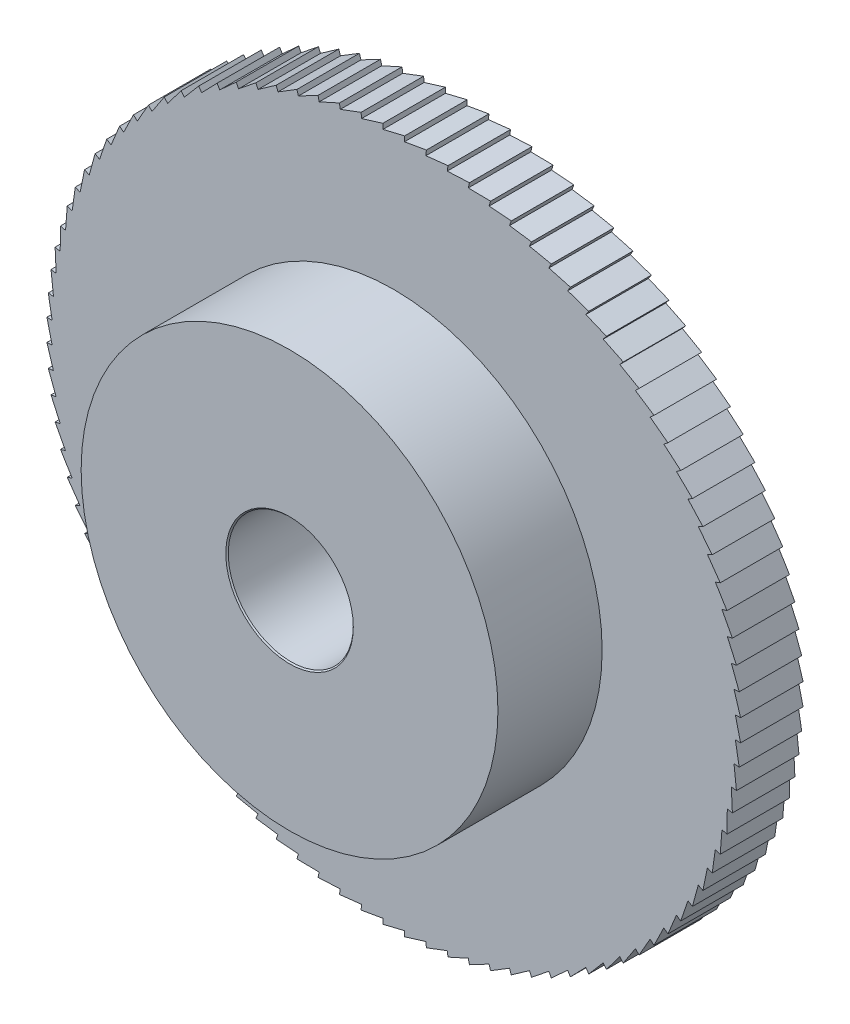
SolidWorks part; units mm, degrees
ref_plane "Front" through (0, 0, 0) normal (0, 0, 1) x (1, 0, 0)
ref_plane "Top" through (0, 0, 0) normal (0, 1, 0) x (1, 0, 0)
ref_plane "Right" through (0, 0, 0) normal (1, 0, 0) x (0, 0, -1)
sketch "Sketch1" plane through (0, 0, 0) normal (0, 0, 1) x (1, 0, 0)
  line L0 (-50, 0) -> (50, 0) construction
  circle A0 centre (0, 0) radius 33.3 construction
  circle A1 centre (0, 0) radius 3.125 construction
  circle A2 centre (0, 0) radius 6
  circle A3 centre (0, 0) radius 32.8
  point P8 (0, 33.3)
  point P9 (0, -33.3)
  dimension "D1" = 65.6
extrude "Boss-Extrude1" add sketch "Sketch1" against normal blind 6
sketch "Sketch2" plane through (0, 0, 0) normal (0, 0, 1) x (1, 0, 0)
  line L0 (0, 0) -> (0, 33.3) construction
  line L1 (0, 0) -> (-1.0303, 32.7838) construction
  line L2 (0, 0) -> (1.046, 33.2836) construction
  line L3 (-1.0303, 32.7838) -> (1.0303, 32.7838) construction
  line L4 (-1.0303, 32.7838) -> (1.046, 33.2836)
  line L5 (1.046, 33.2836) -> (1.0303, 32.7838)
  circle A0 centre (0, 0) radius 33.3 construction
  circle A2 centre (0, 0) radius 32.8 construction
  arc A4 (1.0303, 32.7838) -> (-1.0303, 32.7838) centre (0, 0) ccw
  point P8 (0, 32.7838)
  point P11 (0, 12.4972)
  dimension "D1" = 3.6
extrude "Boss-Extrude2" add sketch "Sketch2" against normal blind 6
pattern_circular "CirPattern1" count 100 over 360 about axis through (0, 0, 0) along (0, 0, 1) of "Boss-Extrude2"
sketch "Sketch3" plane through (0, 0, 0) normal (0, 0, 1) x (1, 0, 0)
  circle A0 centre (0, 0) radius 20
  circle A1 centre (0, 0) radius 6 construction
  circle A2 centre (0, 0) radius 6
  dimension "Hub Dia" = 40
extrude "Boss-Extrude3" add sketch "Sketch3" along normal blind 10
chamfer "Chamfer1" distance 0.12 angle 45 2 edges at (6, 0, -6) (6, 0, 10)
sketch "Pawl" plane through (0, 0, 0) normal (0, 0, 1) x (1, 0, 0)
  circle A0 centre (0, 0) radius 33.3 construction
  line B0 (28.9467, 41.2833) -> (1.9467, 41.2833)
  line B1 (-1.0533, 38.2833) -> (-1.0533, 33.2833)
  line B2 (-1.0533, 33.2833) -> (4.1429, 36.2833)
  circle B3 centre (28.9467, 33.2833) radius 2.5
  arc B4 (24.0834, 26.9313) -> (28.9467, 41.2833) centre (28.9467, 33.2833) ccw
  arc B5 (4.1429, 36.2833) -> (24.0834, 26.9313) centre (-7.3114, -14.0745) cw
  arc B6 (1.9467, 41.2833) -> (-1.0533, 38.2833) centre (1.9467, 38.2833) ccw
  dimension "Mounting Distance" = 44.11
sketch_block_instance "Block1-1"
sketch_block "Block1" parameters "D1"=5, "D3"=3, "D8"=51.6441, "D2"=60, "D4"=8, "D5"=38, "D6"=30, "D7"=5
sketch "Ref" plane through (0, 0, 0) normal (1, 0, 0) x (0, 0, -1)
  line L0 (-9.88, 6) -> (5.88, 6) construction
  line L1 (5.88, 6) -> (6, 6.12) construction
  line L2 (-9.88, 6) -> (-10, 6.12) construction
  line L3 (-10, -6.12) -> (-9.88, -6) construction
  line L5 (-9.88, -6) -> (5.88, -6) construction
  line L6 (5.88, -6) -> (6, -6.12) construction
equation "\"Pitch Dia@Sketch1\" = \"Teeth@Sketch1\"/16"
equation "\"D1@Boss-Extrude2\" = \"D1@Boss-Extrude1\""
equation "\"D1@CirPattern1\" = \"Teeth@Sketch1\""
equation "\"D1@Chamfer1\" = \"Bore Dia.@Sketch1\"*.01"
equation "\"D1@Sketch1\"=\"OD@Sketch1\"-1"
equation "\"D1@Sketch2\"=360/\"Teeth@Sketch1\""
